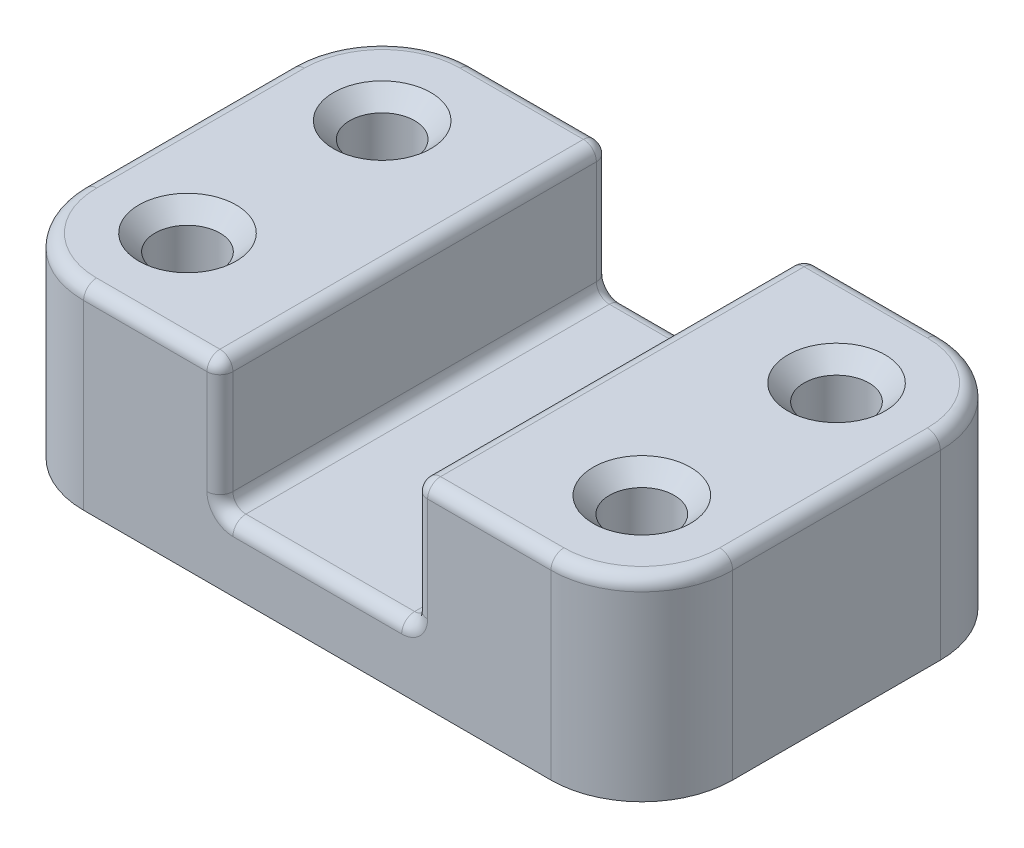
SolidWorks part; units mm, degrees
material "Beech"
ref_plane "Front Plane" through (0, 0, 0) normal (0, 0, 1) x (1, 0, 0)
ref_plane "Top Plane" through (0, 0, 0) normal (0, 1, 0) x (1, 0, 0)
ref_plane "Right Plane" through (0, 0, 0) normal (1, 0, 0) x (0, 0, -1)
sketch "Sketch1" plane through (0, 0, 0) normal (0, 1, 0) x (1, 0, 0)
  line L1 (-63.5, 38.1) -> (63.5, 38.1)
  line L2 (-63.5, 38.1) -> (-63.5, -38.1)
  line L3 (-63.5, -38.1) -> (63.5, -38.1)
  line L4 (63.5, 38.1) -> (63.5, -38.1)
  line L5 (-63.5, 38.1) -> (63.5, -38.1) construction
  line L6 (-63.5, -38.1) -> (63.5, 38.1) construction
  point P0 (0, 0)
  dimension "D1" = 127
  dimension "D2" = 76.2
extrude "Boss-Extrude1" add sketch "Sketch1" along normal blind 38.1
sketch "Sketch2" plane through (0, 38.1, 0) normal (0, 1, 0) x (1, 0, 0)
  line L0 (-63.5, 38.1) -> (-63.5, -38.1) construction
  line L1 (63.5, 38.1) -> (-63.5, 38.1) construction
  line L3 (0, 42.3656) -> (0, -45.2448) construction
  line L4 (-69.444, 0) -> (72.8716, 0) construction
  line L5 (-63.5, -38.1) -> (63.5, -38.1) construction
  circle A0 centre (-44.45, 19.05) radius 6.35
  circle A1 centre (44.45, 19.05) radius 6.35
  circle A2 centre (44.45, -19.05) radius 6.35
  circle A3 centre (-44.45, -19.05) radius 6.35
  point P8 (0, 0)
  point P20 (0, 0)
  dimension "D3" = 12.7
  dimension "D1" = 19.05
  dimension "D2" = 19.05
  dimension "D6" = 88.9
  dimension "D7" = 19.05
  dimension "D4" = 2
  dimension "D5" = 2
extrude "Cut-Extrude2" cut sketch "Sketch2" against normal through all
sketch "Sketch3" plane through (0, 38.1, 0) normal (0, 1, 0) x (1, 0, 0)
  line L0 (0, 45.1077) -> (0, -46.6159) construction
  line L1 (-63.5, -38.1) -> (63.5, -38.1) construction
  line L2 (-19.05, 38.1) -> (19.05, 38.1)
  line L3 (-19.05, 38.1) -> (-19.05, -38.1)
  line L4 (-19.05, -38.1) -> (19.05, -38.1)
  line L5 (19.05, 38.1) -> (19.05, -38.1)
  line L6 (-19.05, 38.1) -> (19.05, -38.1) construction
  line L7 (-19.05, -38.1) -> (19.05, 38.1) construction
  point P3 (0, 0)
  dimension "D1" = 38.1
extrude "Cut-Extrude3" cut sketch "Sketch3" against normal blind 25.4
fillet "Fillet1" radius 17.78 4 edges at (-63.5, 19.05, -38.1) (63.5, 19.05, -38.1) (-63.5, 19.05, 38.1) (63.5, 19.05, 38.1)
chamfer "Chamfer1" distance 3.175 angle 45 4 edges at (44.45, 38.1, -12.7) (44.45, 38.1, 25.4) (-44.45, 38.1, -12.7) (-44.45, 38.1, 25.4)
shell "Shell1" thickness 2.54
fillet "Fillet2" radius 2.54 20 edges at (-19.05, 25.4, 38.1) (19.05, 25.4, 38.1) (-19.05, 25.4, -38.1) (19.05, 25.4, -38.1) (32.385, 38.1, -38.1) (58.2924, 38.1, -32.8924) (63.5, 38.1, 0) (58.2924, 38.1, 32.8924) (-32.385, 38.1, -38.1) (-58.2924, 38.1, -32.8924) (-63.5, 38.1, 0) (-58.2924, 38.1, 32.8924) (0, 12.7, 38.1) (-19.05, 12.7, 0) (0, 12.7, -38.1) (19.05, 12.7, 0) (19.05, 38.1, 0) (32.385, 38.1, 38.1) (-32.385, 38.1, 38.1) (-19.05, 38.1, 0)
